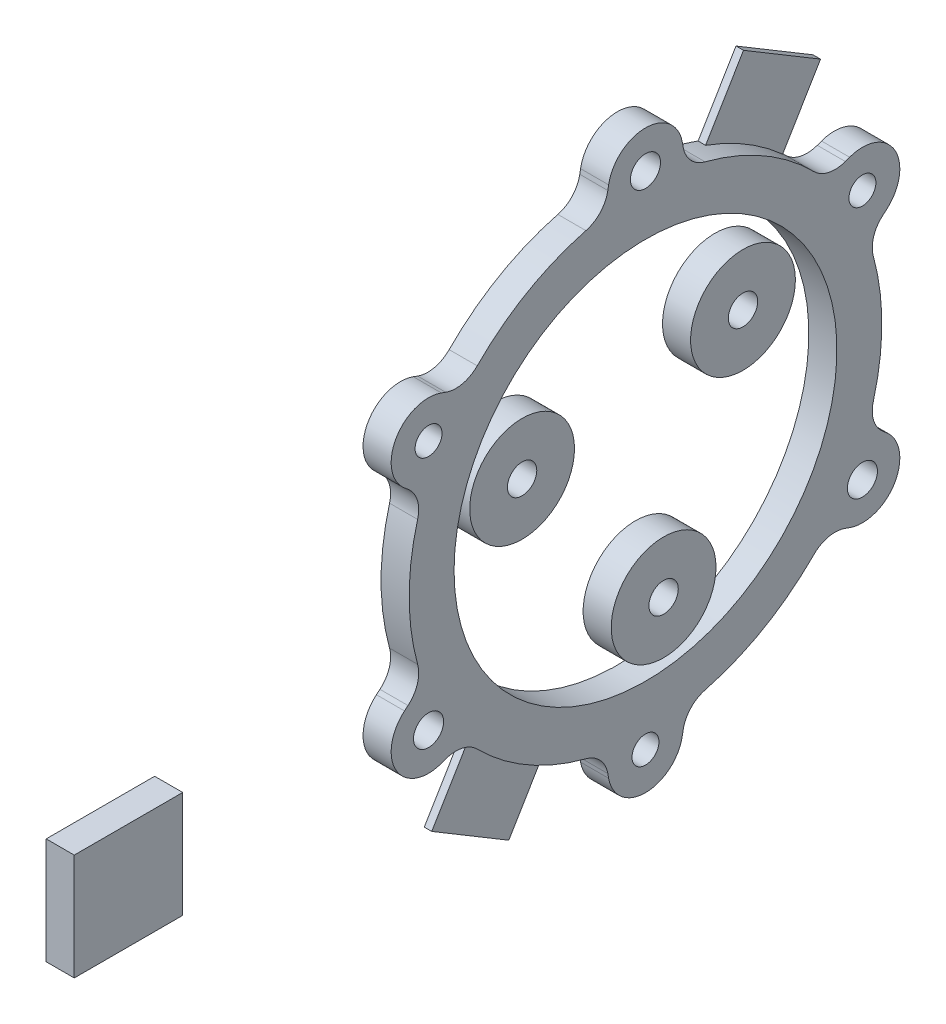
SolidWorks part; units mm, degrees
material "6061-T6 (SS)"
ref_plane "Front Plane" through (0, 0, 0) normal (0, 0, 1) x (1, 0, 0)
ref_plane "Top Plane" through (0, 0, 0) normal (0, 1, 0) x (1, 0, 0)
ref_plane "Right Plane" through (0, 0, 0) normal (1, 0, 0) x (0, 0, -1)
sketch "Sketch1" plane through (0, 0, 0) normal (1, 0, 0) x (0, 0, -1)
  line L0 (0, 42.5) -> (0, -42.5) construction
  line L1 (6.2535, 43.6027) -> (6.9789, 39.489)
  line L2 (-6.2535, 43.6027) -> (-6.9789, 39.489)
  line L3 (16.2405, 28.1293) -> (20.0505, 34.7284)
  line L4 (-20.0505, 34.7284) -> (-16.2405, 28.1293)
  arc A0 (16.2405, 28.1293) -> (-16.2405, 28.1293) centre (0, 0) ccw
  arc A1 (6.2535, 43.6027) -> (-6.2535, 43.6027) centre (0, 42.5) ccw
  arc A2 (20.0505, 34.7284) -> (6.9789, 39.489) centre (0, 0) ccw
  arc A3 (-6.9789, 39.489) -> (-20.0505, 34.7284) centre (0, 0) ccw
  circle A4 centre (0, 0) radius 42.5 construction
  dimension "D1" = 64.9619
  dimension "D6" = 12.7
  dimension "D2" = 85
  dimension "D3" = 7.62
  dimension "D4" = 20
  dimension "D5" = 60
extrude "Boss-Extrude1" add sketch "Sketch1" along normal blind 4.7625
fillet "Fillet1" radius 5.08 2 edges at (2.3813, 39.489, -6.9789) (2.3813, 39.489, 6.9789)
pattern_circular "CirPattern2" count 6 over 360 about axis through (0, 0, 0) along (1, 0, 0) of bodies 101
combine bodies "Combine1" bodies to combine 101 107 108 109 110 111
hole_wizard "#10 Clearance Hole1" positions "Sketch2" profile "Sketch3" hole size "#10" standard "ANSI Inch" end condition through all
sketch "Sketch2" plane through (4.7625, 0, 0) normal (1, 0, 0) x (0, 0, -1)
  point P0 (0, 42.5)
  point P3 (36.8061, -21.25)
  point P6 (-36.8061, -21.25)
sketch "Sketch3" plane through (4.7625, 42.5, 0) normal (0, 1, 0) x (0, 0, -1)
  line L0 (0, 0) -> (0, 4.7625)
  line L1 (0, 4.7625) -> (2.5527, 4.7625)
  line L2 (2.5527, 4.7625) -> (2.5527, 0)
  line L5 (2.5527, 0) -> (0, 0)
  line L11 (0, -6.35) -> (0, 107.95) construction
  dimension "Thru Hole Dia." = 5.1054
  dimension "Thru Hole Depth" = 4.7625
sketch "Sketch4" plane through (4.7625, 0, 0) normal (1, 0, 0) x (0, 0, -1)
  circle A0 centre (-36.8061, 21.25) radius 2.286
  circle A1 centre (36.8061, 21.25) radius 2.286
  circle A2 centre (0, -42.5) radius 2.286
  arc A3 (-6.2535, -43.6027) -> (6.2535, -43.6027) centre (0, -42.5) ccw construction
  arc A4 (40.8878, 16.3856) -> (34.6343, 27.217) centre (36.8061, 21.25) ccw construction
  arc A5 (-34.6343, 27.217) -> (-40.8878, 16.3856) centre (-36.8061, 21.25) ccw construction
  dimension "D1" = 4.572
extrude "Cut-Extrude1" cut sketch "Sketch4" against normal through all
sketch "Sketch5" plane through (4.7625, 0, 0) normal (1, 0, 0) x (0, 0, -1)
  line L0 (-20.9338, 7.74) -> (16.5447, 13.8251) construction
  line L1 (-78.5191, -27.6097) -> (-96.9237, -27.6097)
  line L2 (-78.5191, -27.6097) -> (-78.5191, -9.5479)
  line L3 (-78.5191, -9.5479) -> (-96.9237, -9.5479)
  line L4 (-96.9237, -27.6097) -> (-96.9237, -9.5479)
  line L5 (-78.5191, -27.6097) -> (-96.9237, -9.5479) construction
  line L6 (-78.5191, -9.5479) -> (-96.9237, -27.6097) construction
  line L7 (16.5447, 13.8251) -> (3.0753, -21.6748) construction
  line L8 (3.0753, -21.6748) -> (-20.9338, 7.74) construction
  circle A0 centre (-20.9338, 7.74) radius 8.89
  circle A1 centre (3.0753, -21.6748) radius 8.89
  circle A2 centre (-20.9338, 7.74) radius 2.4892
  circle A3 centre (3.0753, -21.6748) radius 2.4892
  circle A4 centre (16.5447, 13.8251) radius 2.4892
  circle A5 centre (16.5447, 13.8251) radius 8.89
  point P4 (-87.7214, -18.5788)
  dimension "D1" = 4.9784
  dimension "D2" = 17.78
extrude "Boss-Extrude2" add sketch "Sketch5" against normal up to surface (4.7625 mm away) separate body up to face at (0, 21.25, 34.5201)
sketch "Sketch6" plane through (0, 0, 0) normal (-1, 0, 0) x (0, 0, 1)
  line L0 (26.7647, -29.862) -> (13.6899, -37.6918)
  line L1 (26.7647, -29.862) -> (32.7739, -39.8965)
  line L2 (13.6899, -37.6918) -> (19.6991, -47.7264)
  line L3 (32.7739, -39.8965) -> (19.6991, -47.7264)
  line L4 (-26.7647, 29.862) -> (-13.6899, 37.6918)
  line L5 (-26.7647, 29.862) -> (-33.1981, 40.6048)
  line L6 (-13.6899, 37.6918) -> (-20.1233, 48.4347)
  line L7 (-33.1981, 40.6048) -> (-20.1233, 48.4347)
  arc A0 (10.1102, -38.8055) -> (28.5515, -28.1585) centre (0, 0) ccw construction
  arc A1 (-10.1102, 38.8055) -> (-28.5515, 28.1585) centre (0, 0) ccw construction
  dimension "D1" = 15.24
extrude "Boss-Extrude3" add sketch "Sketch6" against normal blind 1.27
equation "\"D1@Sketch1\"=65mm-.0015"
